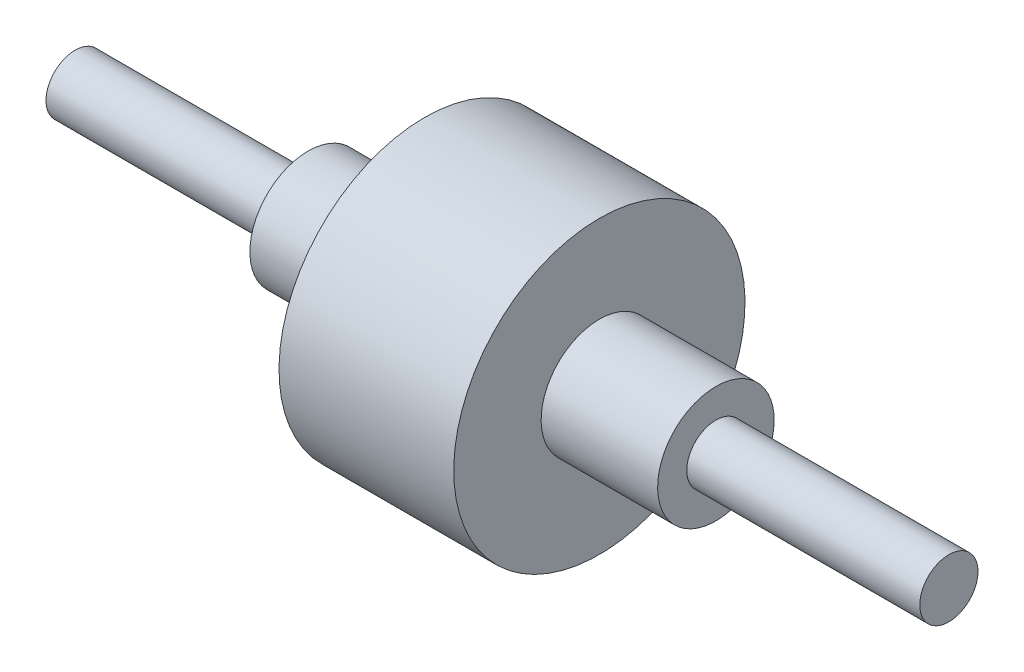
SolidWorks part; units mm, degrees
ref_plane "Alzado" through (0, 0, 0) normal (0, 0, 1) x (1, 0, 0)
ref_plane "Planta" through (0, 0, 0) normal (0, 1, 0) x (1, 0, 0)
ref_plane "Vista lateral" through (0, 0, 0) normal (1, 0, 0) x (0, 0, -1)
sketch "Croquis1" plane through (0, 0, 0) normal (0, 0, 1) x (1, 0, 0)
  line L0 (-150, 0) -> (150, 0) construction
  line L1 (150, 0) -> (150, 10)
  line L2 (150, 10) -> (70, 10)
  line L3 (70, 10) -> (70, 20)
  line L4 (70, 20) -> (30, 20)
  line L5 (30, 20) -> (30, 50)
  line L6 (30, 50) -> (-30, 50)
  line L7 (0, 50) -> (0, 0) construction
  line L8 (-30, 20) -> (-30, 50)
  line L9 (-70, 20) -> (-30, 20)
  line L10 (-70, 10) -> (-70, 20)
  line L11 (-150, 10) -> (-70, 10)
  line L12 (-150, 0) -> (-150, 10)
  line L13 (150, 0) -> (-150, 0)
  dimension "D1" = 10
  dimension "D2" = 20
  dimension "D3" = 50
  dimension "D4" = 150
  dimension "D5" = 80
  dimension "D6" = 40
revolve "Revolución2" add sketch "Croquis1" angle 360 about L13
equation "\"A\" = 10mm"
equation "\"D1@Croquis1\"=\"A\""
equation "\"D2@Croquis1\"=\"D1@Croquis1\"*2"
equation "\"D3@Croquis1\"=\"A\"*5"
equation "\"D5@Croquis1\"=\"D1@Croquis1\"*8"
equation "\"D6@Croquis1\"=\"D1@Croquis1\"*4"
equation "\"D4@Croquis1\"=\"D1@Croquis1\"*15"
